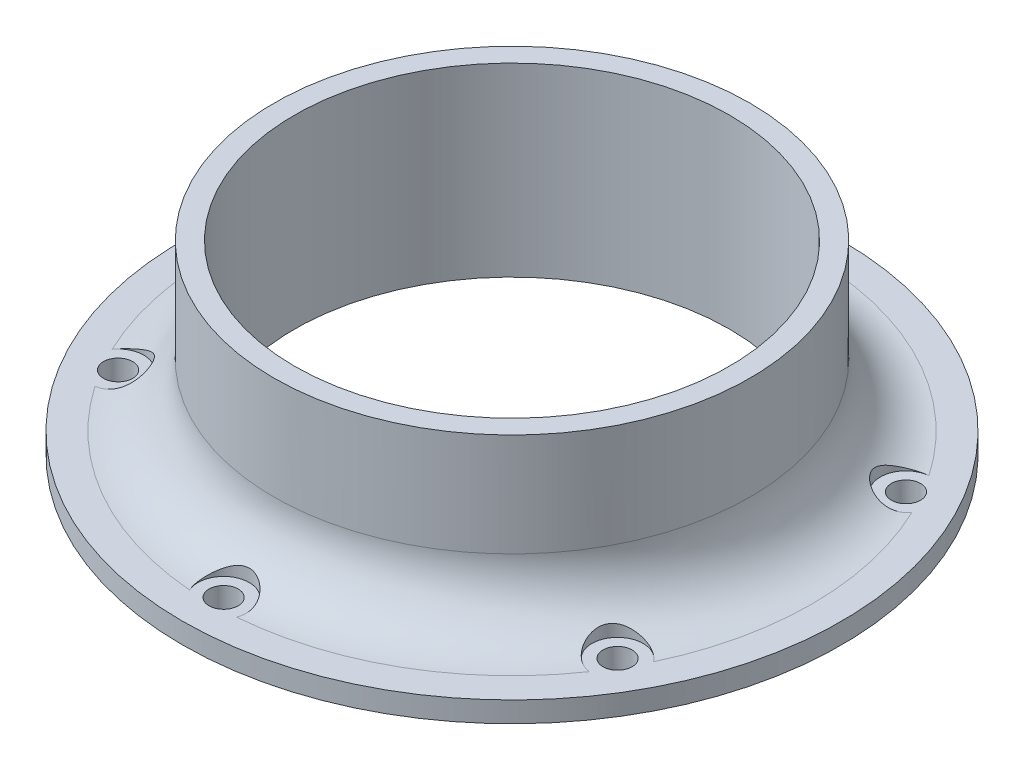
SolidWorks part; units mm, degrees
material "6061 Alloy"
ref_plane "Front Plane" through (0, 0, 0) normal (0, 0, 1) x (1, 0, 0)
ref_plane "Top Plane" through (0, 0, 0) normal (0, 1, 0) x (1, 0, 0)
ref_plane "Right Plane" through (0, 0, 0) normal (1, 0, 0) x (0, 0, -1)
sketch "Sketch1" plane through (0, 0, 0) normal (0, 1, 0) x (1, 0, 0)
  circle A0 centre (0, 0) radius 33.528
  circle A1 centre (0, 0) radius 36.703
  dimension "D1" = 67.056
  dimension "D2" = 3.175
extrude "Boss-Extrude1" add sketch "Sketch1" along normal blind 25.4
sketch "Sketch2" plane through (0, 0, 0) normal (0, -1, 0) x (1, 0, 0)
  circle A0 centre (0, 0) radius 33.528
  circle A1 centre (0, 0) radius 50.8
  circle A2 centre (0, 0) radius 33.528 construction
  dimension "D1" = 101.6
extrude "Boss-Extrude2" add sketch "Sketch2" along normal blind 3.175
fillet "Fillet1" radius 9.525 1 edges at (0, 0, -36.703)
hole_wizard "#8 Clearance Hole1" positions "Sketch4" profile "Sketch5" hole size "#8" standard "Ansi Inch"
sketch "Sketch4" plane through (0, 0, 0) normal (0, 1, 0) x (-1, 0, 0)
  point P0 (0, -44.45)
  dimension "D1" = 44.45
sketch "Sketch5" plane through (0, 0, -44.45) normal (1, 0, 0) x (0, 0, 1)
  line L0 (0, 0) -> (0, 3.175)
  line L1 (0, 3.175) -> (2.2479, 3.175)
  line L2 (2.2479, 3.175) -> (2.2479, 0)
  line L5 (2.2479, 0) -> (0, 0)
  line L11 (0, -6.35) -> (0, 107.95) construction
  dimension "Thru Hole Dia." = 4.4958
  dimension "Thru Hole Depth" = 3.175
pattern_circular "CirPattern1" count 6 over 360 about axis through (0, 0, 0) along (0, 1, 0) of "#8 Clearance Hole1"
sketch "Sketch6" plane through (0, 0, 0) normal (0, 1, 0) x (1, 0, 0)
  circle A0 centre (0, 44.45) radius 3.9624
  dimension "D1" = 7.9248
extrude "Cut-Extrude1" cut sketch "Sketch6" along normal blind 52.07
pattern_circular "CirPattern2" count 6 over 360 about axis through (0, 0, 0) along (0, 1, 0) of "Cut-Extrude1"
